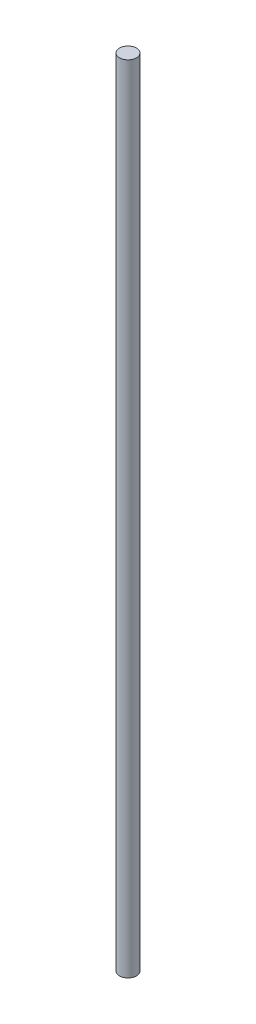
SolidWorks part; units mm, degrees
ref_plane "Front" through (0, 0, 0) normal (0, 0, 1) x (1, 0, 0)
ref_plane "Top" through (0, 0, 0) normal (0, 1, 0) x (1, 0, 0)
ref_plane "Right" through (0, 0, 0) normal (1, 0, 0) x (0, 0, -1)
sketch "Sketch1" plane through (0, 0, 0) normal (0, 1, 0) x (1, 0, 0)
  circle A0 centre (0, 0) radius 4
  dimension "D1" = 8
extrude "Boss-Extrude1" add sketch "Sketch1" along normal blind 375
equation "\"length\"=375"
equation "\"D1@Boss-Extrude1\"= \"length\""
